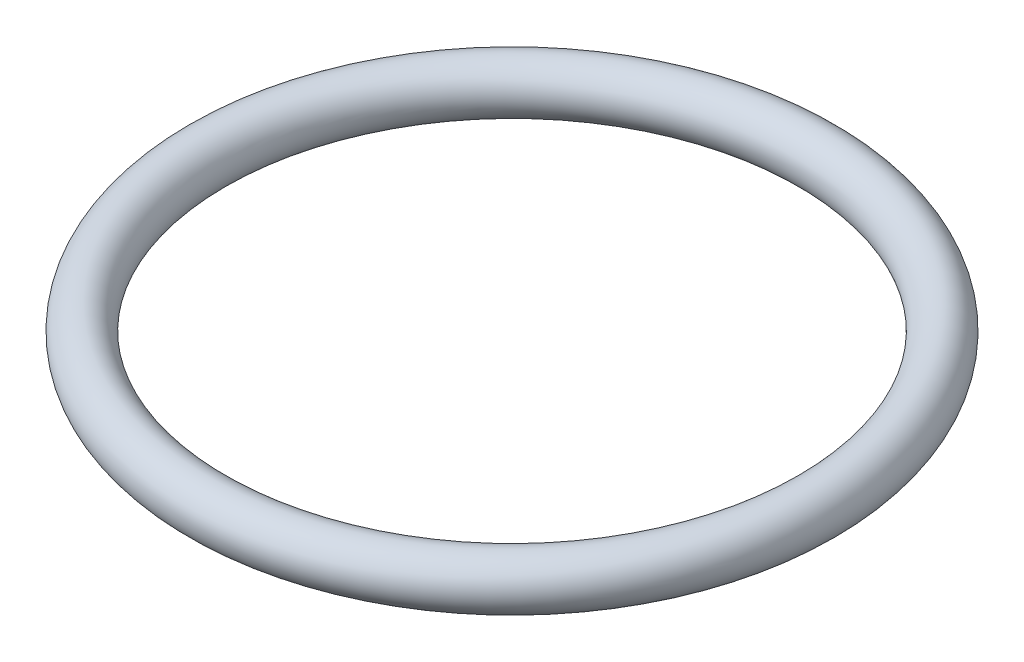
SolidWorks part; units mm, degrees
material "Резина"
ref_plane "Спереди" through (0, 0, 0) normal (0, 0, 1) x (1, 0, 0)
ref_plane "Сверху" through (0, 0, 0) normal (0, 1, 0) x (1, 0, 0)
ref_plane "Справа" through (0, 0, 0) normal (1, 0, 0) x (0, 0, -1)
sketch "Эскиз1" plane through (0, 0, 0) normal (0, 0, 1) x (1, 0, 0)
  line L0 (-245.2086, 0) -> (12015.2196, 0) construction
  line L1 (0, -245.2086) -> (0, 12015.2196) construction
  circle A0 centre (-60, 0) radius 5
  dimension "D1" = 10
  dimension "D2" = 55
revolve "Повернуть1" add sketch "Эскиз1" angle 360 about L1
